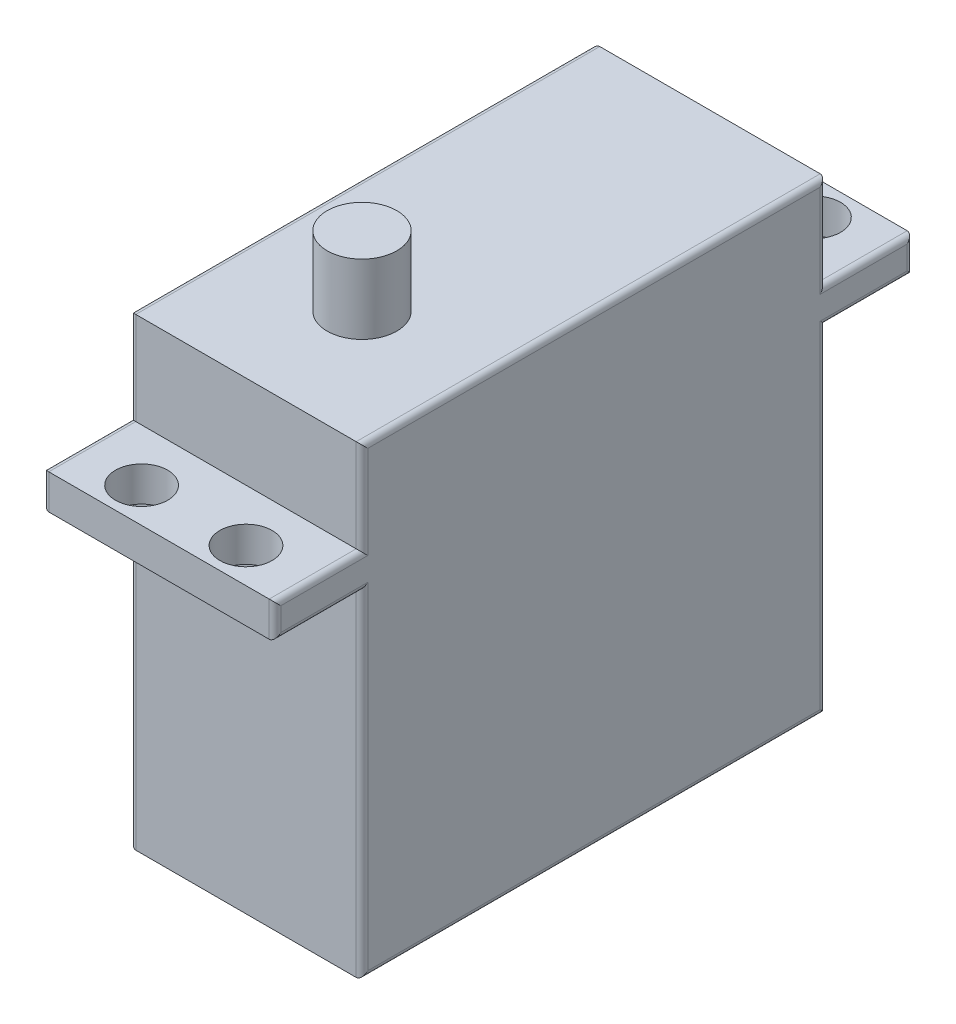
SolidWorks part; units mm, degrees
ref_plane "前视基准面" through (0, 0, 0) normal (0, 0, 1) x (1, 0, 0)
ref_plane "上视基准面" through (0, 0, 0) normal (0, 1, 0) x (1, 0, 0)
ref_plane "右视基准面" through (0, 0, 0) normal (1, 0, 0) x (0, 0, -1)
other "Configuration Table"
sketch "草图1" plane through (0, 0, 0) normal (1, 0, 0) x (0, 0, -1)
  line L1 (-20, 20) -> (20, 20)
  line L2 (-20, 20) -> (-20, -20)
  line L3 (-20, -20) -> (20, -20)
  line L4 (20, 20) -> (20, -20)
  dimension "D1" = 40
  dimension "D2" = 20
  dimension "D3" = 20
extrude "凸台-拉伸1" add sketch "草图1" along normal blind 20
sketch "草图2" plane through (0, 20, 0) normal (0, 1, 0) x (1, 0, 0)
  line L0 (20, 20) -> (20, -20) construction
  line L1 (20, -20) -> (0, -20) construction
  circle A0 centre (10, -10) radius 3
  dimension "D1" = 6
  dimension "D2" = 10
  dimension "D3" = 10
extrude "凸台-拉伸2" add sketch "草图2" along normal blind 6
sketch "草图3" plane through (0, 20, 0) normal (0, 1, 0) x (1, 0, 0)
  line L0 (0, 0) -> (50000, 0) construction
  line L1 (0, -20) -> (20, -20)
  line L2 (0, -20) -> (0, -27.5)
  line L3 (0, -27.5) -> (20, -27.5)
  line L4 (20, -20) -> (20, -27.5)
  line L5 (0, 20) -> (0, -20) construction
  line L6 (20, 20) -> (20, -20) construction
  line L8 (0, 20) -> (20, 20)
  line L9 (0, 20) -> (0, 27.5)
  line L10 (0, 27.5) -> (20, 27.5)
  line L11 (20, 20) -> (20, 27.5)
  point P9 (0, 0)
  dimension "D1" = 7.5
  dimension "D2" = 7.5
extrude "凸台-拉伸3" add sketch "草图3" against normal blind 3 from offset 8 offset against normal yes
sketch "草图4" plane through (0, 12, 0) normal (0, 1, 0) x (1, 0, 0)
  line L0 (0, -27.5) -> (20, -27.5) construction
  line L1 (20, -27.5) -> (20, -20) construction
  line L2 (0, 0) -> (50000, 0) construction
  line L3 (0, 20) -> (0, -20) construction
  circle A0 centre (14.5, -24.5) radius 2.25
  circle A1 centre (5.5, -24.5) radius 2.25
  circle A2 centre (5.5, 24.5) radius 2.25
  circle A3 centre (14.5, 24.5) radius 2.25
  point P12 (0, 0)
  dimension "D1" = 4.5
  dimension "D2" = 9
  dimension "D3" = 3
  dimension "D4" = 5.5
extrude "切除-拉伸1" cut sketch "草图4" against normal blind 3
fillet "圆角1" radius 0.5 24 edges at (0, 20, 0) (20, 20, 0) (20, 16, -20) (0, 16, -20) (20, 12, -23.75) (20, 10.5, -27.5) (20, 9, -23.75) (20, -5.5, -20) (0, -5.5, -20) (0, -20, 0) (20, -20, 0) (20, -5.5, 20) (0, -5.5, 20) (20, 9, 23.75) (20, 10.5, 27.5) (20, 12, 23.75) (20, 16, 20) (0, 16, 20) (0, 12, 23.75) (0, 10.5, 27.5) (0, 9, 23.75) (0, 9, -23.75) (0, 10.5, -27.5) (0, 12, -23.75)
